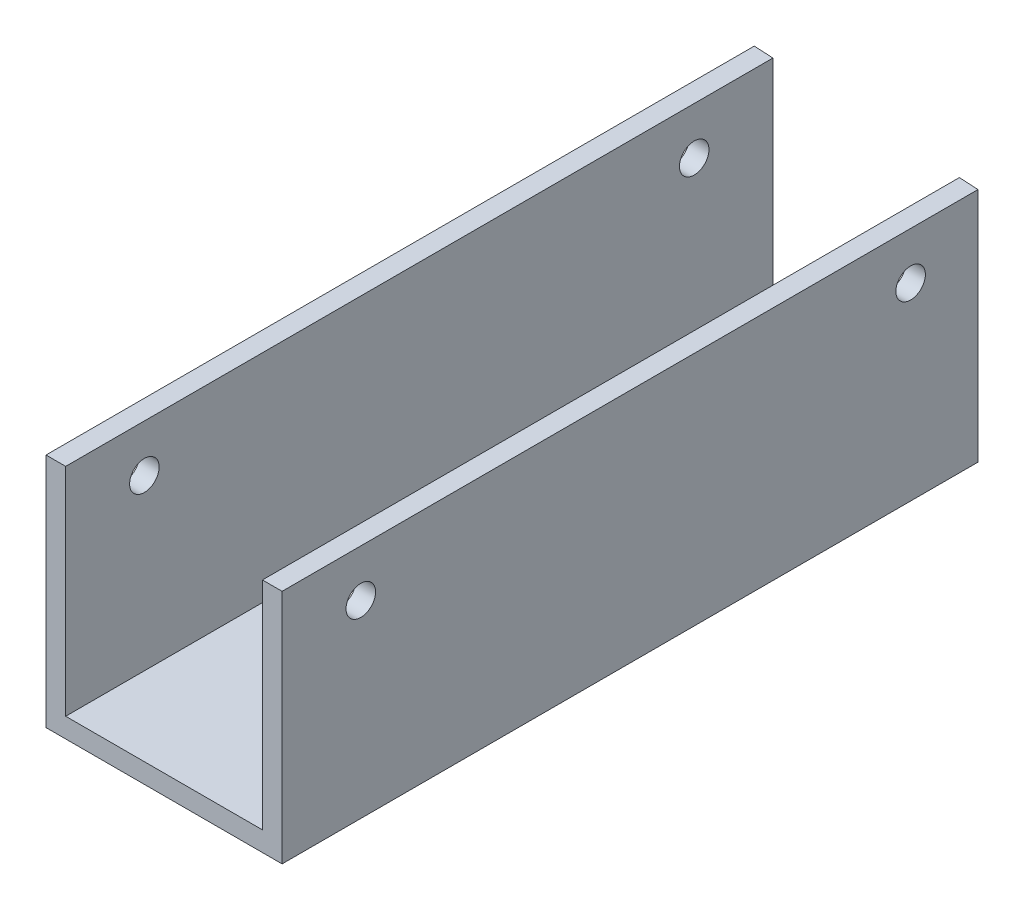
SolidWorks part; units mm, degrees
ref_plane "Front Plane" through (0, 0, 0) normal (0, 0, 1) x (1, 0, 0)
ref_plane "Top Plane" through (0, 0, 0) normal (0, 1, 0) x (1, 0, 0)
ref_plane "Right Plane" through (0, 0, 0) normal (1, 0, 0) x (0, 0, -1)
sketch "Sketch1" plane through (0, 0, 0) normal (0, 0, 1) x (1, 0, 0)
  line L0 (18.3712, 0) -> (-19.7288, 0)
  line L1 (-19.7288, 0) -> (-19.7288, 38.1)
  line L2 (-19.7288, 38.1) -> (-16.5538, 38.1)
  line L3 (-16.5538, 38.1) -> (-16.5538, 3.175)
  line L4 (-16.5538, 3.175) -> (15.1962, 3.175)
  line L5 (15.1962, 3.175) -> (15.1962, 38.1)
  line L6 (15.1962, 38.1) -> (18.3712, 38.1)
  line L7 (18.3712, 38.1) -> (18.3712, 0)
  dimension "D1" = 3.175
  dimension "D2" = 3.175
  dimension "D3" = 3.175
  dimension "D4" = 38.1
  dimension "D5" = 38.1
  dimension "D6" = 38.1
extrude "Boss-Extrude1" add sketch "Sketch1" along normal blind 114.3
sketch "Sketch2" plane through (0, 38.1, 0) normal (0, 1, 0) x (1, 0, 0)
  line L0 (-19.7288, 0) -> (18.3712, 0)
  line L1 (18.3712, 0) -> (18.3712, -1.9967)
  line L2 (18.3712, -114.3) -> (18.3712, 0) construction
  line L3 (18.3712, -1.9967) -> (-19.7288, 0)
  dimension "D1" = 3
extrude "Cut-Extrude1" cut sketch "Sketch2" against normal blind 98.425
sketch "Sketch3" plane through (18.3712, 0, 0) normal (1, 0, 0) x (0, 0, -1)
  line L0 (-114.3, 0) -> (-114.3, 38.1) construction
  line L1 (-0.1664, 3.175) -> (-0.1664, 38.1) construction
  line L2 (-114.3, 0) -> (-1.9967, 0) construction
  circle A0 centre (-12.8664, 30.48) radius 2.3813
  circle A1 centre (-101.6, 30.48) radius 2.3813
  dimension "D5" = 4.7625
  dimension "D1" = 12.7
  dimension "D2" = 12.7
  dimension "D3" = 30.48
  dimension "D4" = 30.48
extrude "Cut-Extrude2" cut sketch "Sketch3" against normal blind 98.425
sketch "Sketch4" plane through (0, 3.175, 0) normal (0, 1, 0) x (1, 0, 0)
  line L0 (-16.5538, -114.3) -> (-16.5538, -0.1664) construction
  line L1 (-16.5538, -68.2625) -> (15.1962, -68.2625)
  line L2 (-16.5538, -68.2625) -> (-16.5538, -76.2)
  line L3 (-16.5538, -76.2) -> (15.1962, -76.2)
  line L4 (15.1962, -68.2625) -> (15.1962, -76.2)
  line L5 (15.1962, -114.3) -> (15.1962, -1.8303) construction
  line L7 (15.1962, -114.3) -> (-16.5538, -114.3) construction
  dimension "D1" = 7.9375
  dimension "D2" = 38.1
extrude "Cut-Extrude4" cut sketch "Sketch4" against normal through all
